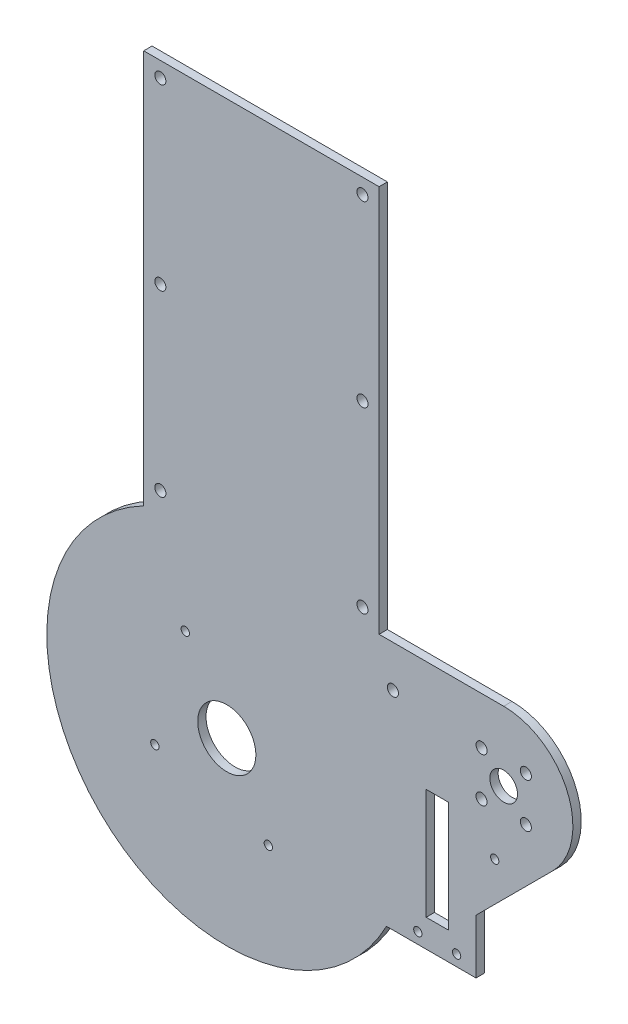
SolidWorks part; units mm, degrees
ref_plane "前视基准面" through (0, 0, 0) normal (0, 0, 1) x (1, 0, 0)
ref_plane "上视基准面" through (0, 0, 0) normal (0, 1, 0) x (1, 0, 0)
ref_plane "右视基准面" through (0, 0, 0) normal (1, 0, 0) x (0, 0, -1)
sketch "Sketch1" plane through (0, 0, 0) normal (0, 0, 1) x (1, 0, 0)
  line L0 (-10.9179, 60) -> (113.3582, 60) construction
  line L3 (-33.1662, 50) -> (-60, 50)
  line L4 (-60, 0) -> (-60, 50)
  line L6 (56.8821, -30) -> (90, -30)
  line L7 (90, -10.3553) -> (117.6777, 17.3223)
  line L13 (0, 60) -> (100, 60)
  line L14 (76, 5.7859) -> (76, -20.6668) construction
  line L16 (72, 20) -> (80, 20)
  line L17 (72, 20) -> (72, -20)
  line L18 (72, -20) -> (80, -20)
  line L19 (80, 20) -> (80, -20)
  line L20 (72, 20) -> (80, -20) construction
  line L21 (72, -20) -> (80, 20) construction
  line L25 (90, -30) -> (90, -10.3553)
  line L26 (56.8821, -30) -> (51.9615, -30)
  line L27 (57.5629, -26) -> (85.1685, -26) construction
  arc A0 (0, 60) -> (51.9615, -30) centre (0, 0) ccw
  circle A2 centre (0, 0) radius 10.5
  arc A8 (117.6777, 17.3223) -> (100, 60) centre (100, 35) ccw
  circle A9 centre (100, 35) radius 5
  circle A11 centre (69, -26) radius 1.5
  circle A12 centre (83, -26) radius 1.5
  point P21 (76, 0)
  dimension "D1" = 120
  dimension "D2" = 90
  dimension "D3" = 21
  dimension "D5" = 50
  dimension "D4" = 100
  dimension "D6" = 10
  dimension "D12" = 7
  dimension "D7" = 10
  dimension "D8" = 8
  dimension "D9" = 40
  dimension "D10" = 150
  dimension "D11" = 6
extrude "Boss-Extrude1" add sketch "Sketch1" along normal blind 3
sketch "Sketch2" plane through (0, 0, 3) normal (0, 0, 1) x (1, 0, 0)
  line L1 (-60, 0) -> (-60, 50) construction
  line L2 (0, 60) -> (100, 60) construction
  circle A1 centre (0, 0) radius 57
  circle A2 centre (60, 45) radius 2
  circle A6 centre (100, 35) radius 14
  dimension "D1" = 15
  dimension "D5" = 28
  dimension "D2" = 120
extrude "Cut-Extrude1" cut sketch "Sketch2" against normal up to next
sketch "Sketch3" plane through (0, 0, 0) normal (0, 0, -1) x (-1, 0, 0)
  line L4 (-30, 0) -> (-30, 80)
  line L5 (-30, 80) -> (5, 80)
  line L6 (5, 80) -> (5, 48)
  line L7 (5, 48) -> (25.3049, 16.1141)
  circle A2 centre (0, 0) radius 10.5
  arc A4 (-30, 0) -> (25.3049, 16.1141) centre (0, 0) ccw
  dimension "D1" = 80
  dimension "D2" = 35
  dimension "D3" = 32
extrude "Boss-Extrude2" add sketch "Sketch3" against normal blind 3
sketch "Sketch4" plane through (0, 0, 0) normal (0, 0, -1) x (-1, 0, 0)
  line L0 (-30, 80) -> (5, 80) construction
  line L1 (5, 80) -> (5, 48) construction
  line L3 (-20, 65.5961) -> (-5, 65.5961)
  line L4 (-20, 65.5961) -> (-20, 63.5961)
  line L5 (-20, 63.5961) -> (-5, 63.5961)
  line L6 (-5, 65.5961) -> (-5, 63.5961)
  line L7 (-20, 65.5961) -> (-5, 63.5961) construction
  line L8 (-20, 63.5961) -> (-5, 65.5961) construction
  line L9 (-13.5, 72.0961) -> (-11.5, 72.0961)
  line L10 (-13.5, 72.0961) -> (-13.5, 57.0961)
  line L11 (-13.5, 57.0961) -> (-11.5, 57.0961)
  line L12 (-11.5, 72.0961) -> (-11.5, 57.0961)
  line L13 (-13.5, 72.0961) -> (-11.5, 57.0961) construction
  line L14 (-13.5, 57.0961) -> (-11.5, 72.0961) construction
  point P5 (-12.5, 64.5961)
  point P10 (-12.5, 80)
  point P11 (-12.5, 64.5961)
  dimension "D1" = 15
  dimension "D2" = 2
  dimension "D3" = 0
  dimension "D4" = 15
  dimension "D5" = 2
extrude "Boss-Extrude3" add sketch "Sketch4" along normal blind 1 contours L12 L9 L10 L3 | L10 L3 L4 L5 | L12 L3 L10 L5 | L3 L12 L5 L6 | L12 L5 L10 L11
sketch "Sketch5" plane through (0, 0, 3) normal (0, 0, 1) x (1, 0, 0)
  line L0 (100, 48.4826) -> (100, 24.1919) construction
  line L1 (89.5844, 35) -> (110.5191, 35) construction
  circle A0 centre (92, 43) radius 2
  circle A1 centre (108, 43) radius 2
  circle A2 centre (108, 27) radius 2
  circle A3 centre (92, 27) radius 2
  dimension "D1" = 8
  dimension "D2" = 8
extrude "Cut-Extrude2" cut sketch "Sketch5" against normal blind 10
sketch "Sketch6" plane through (0, 0, 3) normal (0, 0, 1) x (1, 0, 0)
  line L0 (12.5, 60) -> (12.5, 200) construction
  line L1 (30, 80) -> (-5, 80) construction
  line L2 (12.5, 60) -> (55, 60)
  line L3 (-30, 60) -> (-30, 200)
  line L4 (-30, 200) -> (55, 200)
  line L5 (55, 60) -> (55, 200)
  line L6 (-30, 60) -> (55, 200) construction
  line L7 (-30, 200) -> (55, 60) construction
  line L8 (-30, 60) -> (-30, 51.9615)
  line L9 (12.5, 60) -> (-5, 60)
  line L10 (-5, 80) -> (-5, 59.7913) construction
  line L11 (-5, 60) -> (-5, 59.7913)
  arc A0 (-5, 59.7913) -> (-33.1662, 50) centre (0, 0) ccw construction
  arc A1 (-5, 59.7913) -> (-30, 51.9615) centre (0, 0) ccw
  point P2 (12.5, 130)
  point P10 (12.5, 80)
  dimension "D1" = 85
extrude "Boss-Extrude4" add sketch "Sketch6" against normal up to surface (3 mm away) up to face at (94, 27, 0)
sketch "Sketch7" plane through (0, 0, 3) normal (0, 0, 1) x (1, 0, 0)
  line L0 (55, 130) -> (-30, 130) construction
  line L1 (55, 60) -> (55, 200) construction
  line L2 (-30, 200) -> (-30, 51.9615) construction
  line L3 (12.5, 200) -> (12.5, 60) construction
  line L4 (55, 200) -> (-30, 200) construction
  circle A0 centre (-24, 194.5) radius 2
  circle A1 centre (49, 194.5) radius 2
  circle A2 centre (49, 65.5) radius 2
  circle A3 centre (-24, 65.5) radius 2
  circle A4 centre (-24, 130) radius 2
  circle A5 centre (49, 130) radius 2
  dimension "D1" = 4
  dimension "D2" = 4
  dimension "D3" = 6
  dimension "D4" = 5.5
  dimension "D5" = 5.5
  dimension "D6" = 6
extrude "Cut-Extrude3" cut sketch "Sketch7" against normal blind 10
sketch "Sketch8" plane through (0, 0, 3) normal (0, 0, 1) x (1, 0, 0)
  circle A0 centre (0, 0) radius 65
  circle A1 centre (0, 0) radius 10.5
extrude "Boss-Extrude5" add sketch "Sketch8" against normal up to surface (3 mm away) up to face at (51, 194.5, 0)
sketch "Sketch9" plane through (0, 0, 3) normal (0, 0, 1) x (1, 0, 0)
  line L0 (-60, 50) -> (-60, 25)
  line L1 (-60, 50) -> (-41.5331, 50)
  arc A0 (-41.5331, 50) -> (-60, 25) centre (0, 0) ccw
extrude "Cut-Extrude4" cut sketch "Sketch9" against normal blind 10
sketch "Sketch10" plane through (0, 0, 3) normal (0, 0, 1) x (1, 0, 0)
  circle A0 centre (-15, 25.9808) radius 1.5
  circle A1 centre (-25.9808, -15) radius 1.5
  circle A2 centre (15, -25.9808) radius 1.5
  circle A3 centre (96.7678, 10.5546) radius 1.5
extrude "Cut-Extrude5" cut sketch "Sketch10" against normal up to next
